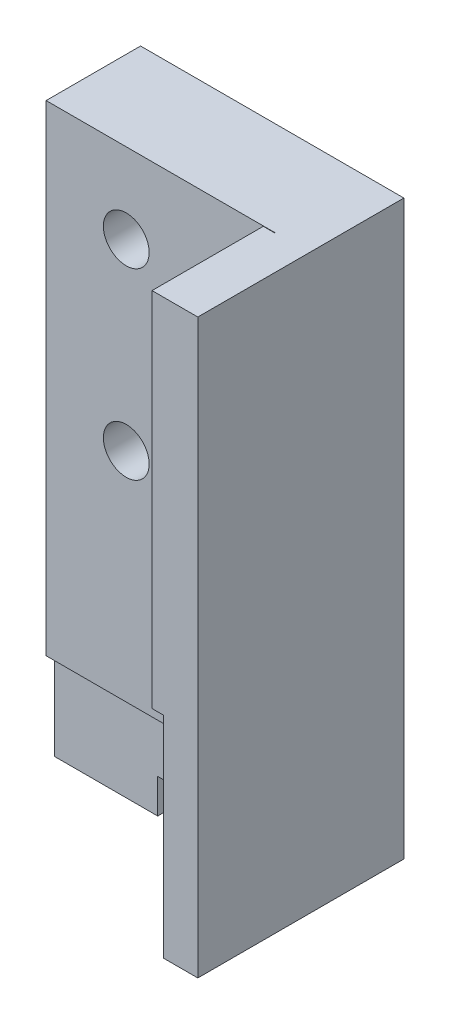
SolidWorks part; units mm, degrees
ref_plane "Front Plane" through (0, 0, 0) normal (0, 0, 1) x (1, 0, 0)
ref_plane "Top Plane" through (0, 0, 0) normal (0, 1, 0) x (1, 0, 0)
ref_plane "Right Plane" through (0, 0, 0) normal (1, 0, 0) x (0, 0, -1)
sketch "Sketch3" plane through (0, 0, 0) normal (0, 1, 0) x (1, 0, 0)
  line L0 (0, 0) -> (0, 9)
  line L1 (0, 9) -> (23, 9)
  line L2 (23, 9) -> (23, -9)
  line L3 (23, -9) -> (20, -9)
  line L4 (20, -9) -> (20, 0)
  line L5 (20, 0) -> (0, 0)
  dimension "D1" = 20
  dimension "D2" = 9
  dimension "D3" = 9
  dimension "D4" = 3
extrude "Boss-Extrude1" add sketch "Sketch3" along normal blind 50
sketch "Sketch4" plane through (0, 0, 0) normal (0, -1, 0) x (1, 0, 0)
  line L0 (20, 0) -> (20, 9) construction
  line L1 (0, 0) -> (20, 0)
  line L2 (0, 0) -> (0, -1.5)
  line L3 (0, -1.5) -> (20, -1.5)
  line L4 (20, 0) -> (20, -1.5)
  dimension "D1" = 1.5
extrude "Cut-Extrude1" cut sketch "Sketch4" against normal blind 8
sketch "Sketch5" plane through (0, 0, 0) normal (0, -1, 0) x (1, 0, 0)
  line L0 (0, -1.5) -> (20, -1.5) construction
  line L1 (20, -1.5) -> (20, 9) construction
  circle A0 centre (5, -5.5) radius 0.5
  circle A1 centre (15, -5.5) radius 0.5
  dimension "D4" = 1
  dimension "D1" = 4
  dimension "D2" = 10
  dimension "D3" = 5
extrude "Cut-Extrude2" cut sketch "Sketch5" against normal blind 8
sketch "Sketch6" plane through (0, 0, -1.5) normal (0, 0, 1) x (1, 0, 0)
  line L0 (0, 0) -> (20, 0) construction
  line L1 (9, 0) -> (12, 0)
  line L2 (9, 0) -> (9, 3)
  line L3 (9, 3) -> (12, 3)
  line L4 (12, 0) -> (12, 3)
  line L5 (20, 8) -> (20, 0) construction
  point P6 (10.5, 0)
  dimension "D1" = 9.5
  dimension "D2" = 3
  dimension "D3" = 3
extrude "Cut-Extrude3" cut sketch "Sketch6" against normal up to surface (7.5 mm away) up to face at (11.5, 25, -9)
sketch "Sketch7" plane through (0, 0, -9) normal (0, 0, -1) x (-1, 0, 0)
  line L0 (-9, 0) -> (0, 0) construction
  line L1 (0, 50) -> (0, 0) construction
  circle A0 centre (-7, 27) radius 2
  circle A1 centre (-7, 43) radius 2
  dimension "D3" = 4
  dimension "D1" = 27
  dimension "D2" = 43
  dimension "D4" = 7
extrude "Cut-Extrude4" cut sketch "Sketch7" against normal up to surface (9 mm away) up to face at (10, 29, 0)
sketch "Sketch8" plane through (0, 0, 0) normal (0, 0, 1) x (1, 0, 0)
  line L4 (0, 8) -> (20, 8)
  line L5 (20, 8) -> (20, 50)
  line L6 (20, 50) -> (0, 50)
  line L7 (0, 50) -> (0, 8)
  line L8 (0, 8) -> (20, 8)
  line L9 (20, 8) -> (20, 50)
  line L10 (20, 50) -> (0, 50)
  line L11 (0, 50) -> (0, 8)
  dimension "D1" = 0
extrude "Cut-Extrude5" cut sketch "Sketch8" against normal blind 0.75
sketch "Sketch9" plane through (20, 0, 0) normal (-1, 0, 0) x (0, 0, 1)
  line L1 (9, 50) -> (-0.72, 50)
  line L2 (9, 50) -> (9, 18.3833)
  line L3 (9, 18.3833) -> (-0.72, 18.3833)
  line L4 (-0.72, 50) -> (-0.72, 18.3833)
extrude "Boss-Extrude2" add sketch "Sketch9" along normal blind 1
